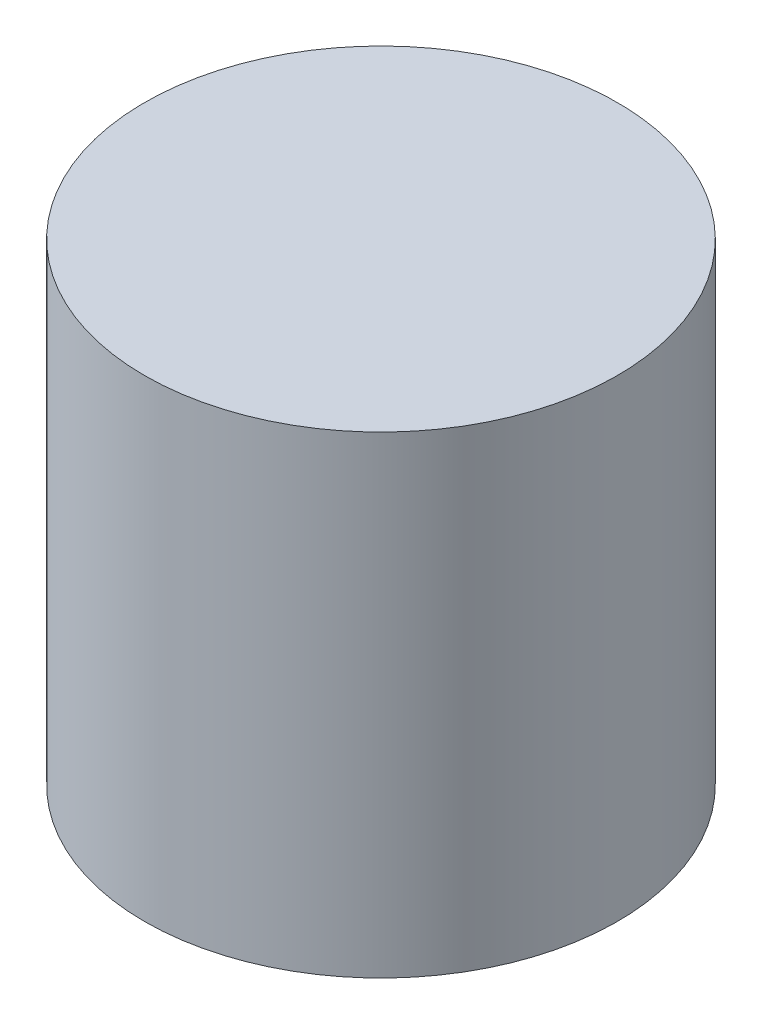
SolidWorks part; units mm, degrees
ref_plane "前视基准面" through (0, 0, 0) normal (0, 0, 1) x (1, 0, 0)
ref_plane "上视基准面" through (0, 0, 0) normal (0, 1, 0) x (1, 0, 0)
ref_plane "右视基准面" through (0, 0, 0) normal (1, 0, 0) x (0, 0, -1)
sketch "草图1" plane through (0, 0, 0) normal (0, 1, 0) x (1, 0, 0)
  circle A0 centre (0, 0) radius 9
extrude "凸台-拉伸1" add sketch "草图1" along normal blind 18
